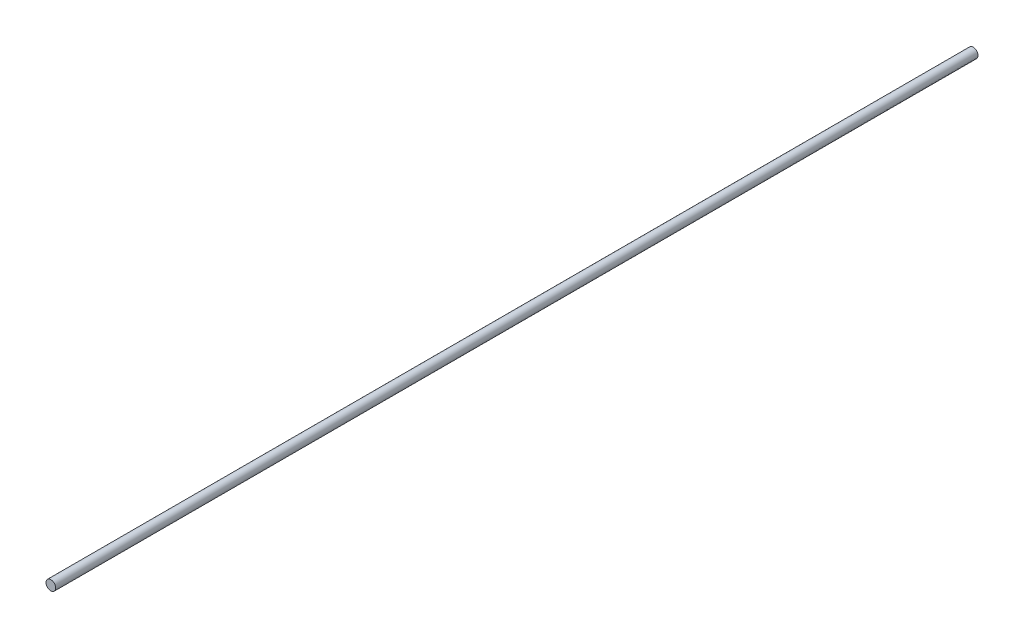
SolidWorks part; units mm, degrees
material "Hexcel AS4C (3000 Filaments)"
ref_plane "Front Plane" through (0, 0, 0) normal (0, 0, 1) x (1, 0, 0)
ref_plane "Top Plane" through (0, 0, 0) normal (0, 1, 0) x (1, 0, 0)
ref_plane "Right Plane" through (0, 0, 0) normal (1, 0, 0) x (0, 0, -1)
sketch "Sketch1" plane through (0, 0, 0) normal (0, 0, 1) x (1, 0, 0)
  circle A0 centre (0, 0) radius 1
extrude "Boss-Extrude1" add sketch "Sketch1" along normal blind 190
